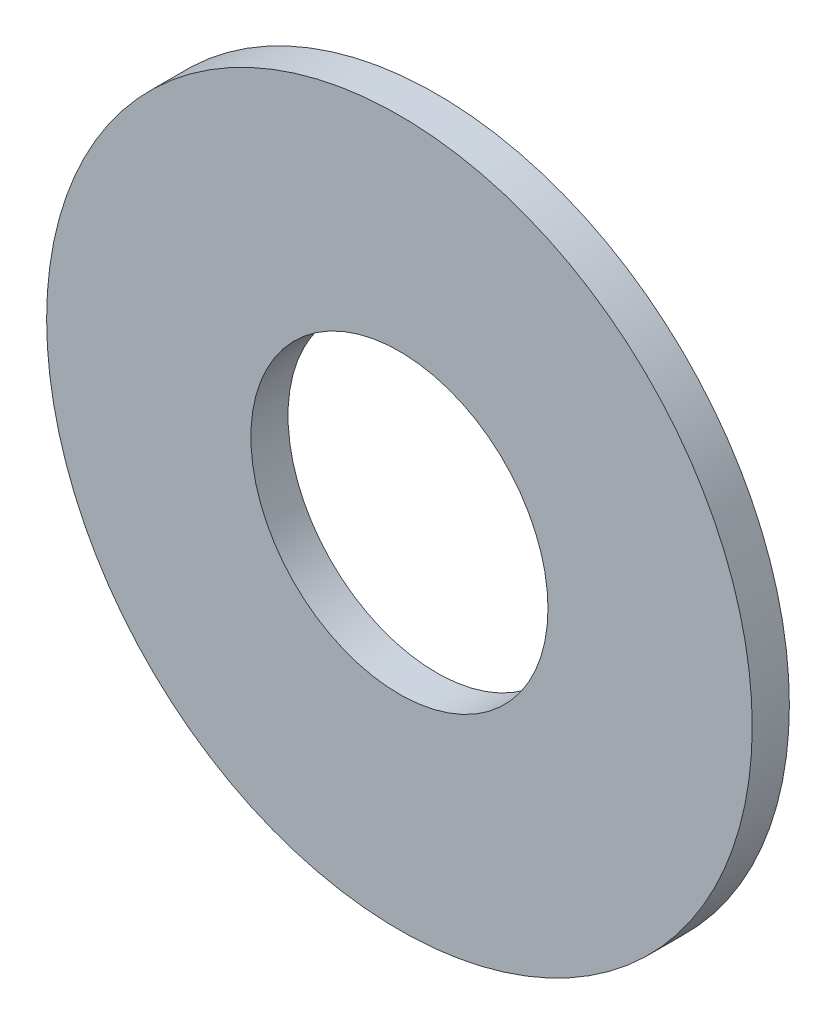
SolidWorks part; units mm, degrees
ref_plane "前视基准面" through (0, 0, 0) normal (0, 0, 1) x (1, 0, 0)
ref_plane "上视基准面" through (0, 0, 0) normal (0, 1, 0) x (1, 0, 0)
ref_plane "右视基准面" through (0, 0, 0) normal (1, 0, 0) x (0, 0, -1)
sketch "草图1" plane through (0, 0, 0) normal (0, 0, 1) x (1, 0, 0)
  circle A0 centre (0, 0) radius 9.5
  circle A1 centre (0, 0) radius 4
  dimension "D1" = 19
extrude "凸台-拉伸1" add sketch "草图1" along normal blind 1
